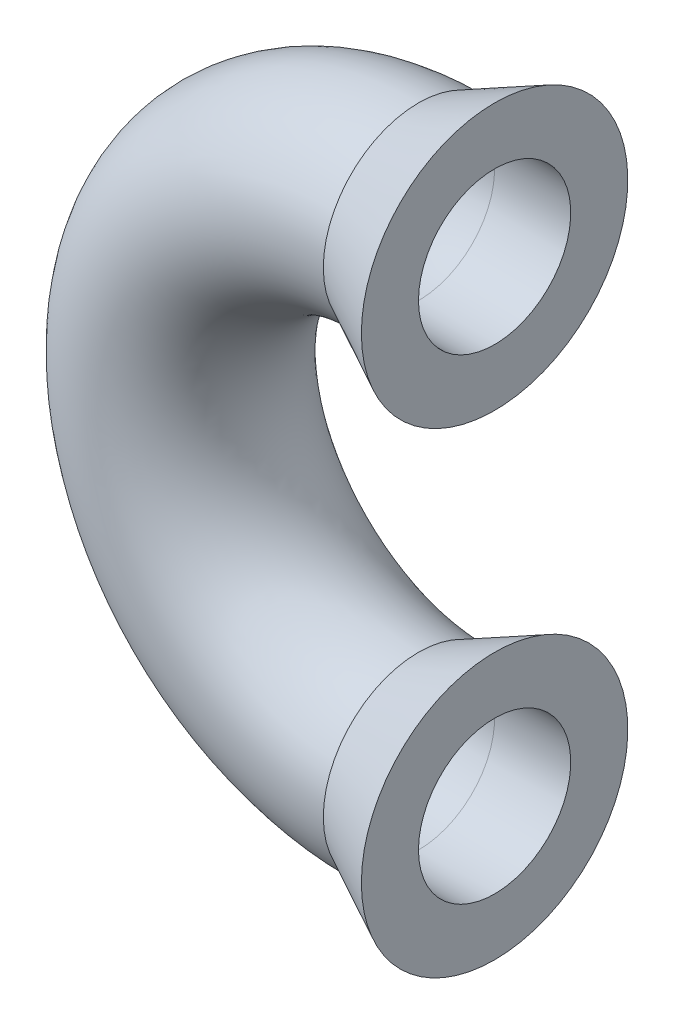
SolidWorks part; units mm, degrees
ref_plane "Спереди" through (0, 0, 0) normal (0, 0, 1) x (1, 0, 0)
ref_plane "Сверху" through (0, 0, 0) normal (0, 1, 0) x (1, 0, 0)
ref_plane "Справа" through (0, 0, 0) normal (1, 0, 0) x (0, 0, -1)
sketch "Эскиз1" plane through (0, 0, 0) normal (0, 0, 1) x (1, 0, 0)
  arc A15 (0, 12.5) -> (0, -12.5) centre (0, 0) ccw
sketch "Эскиз2" plane through (0, 0, 0) normal (1, 0, 0) x (0, 0, -1)
  line L0 (0, 12.5) -> (0, -12.5) construction
  circle A0 centre (0, 12.5) radius 5
  circle A1 centre (0, 12.5) radius 4
  dimension "D1" = 10
  dimension "D2" = 8
sweep "По траектории1" add profiles "Эскиз2" path "Эскиз1"
sketch "Эскиз3" plane through (0, 0, 0) normal (0, 0, 1) x (1, 0, 0)
  line L0 (4, 19.5) -> (0, 17.5)
  line L1 (4, 19.5) -> (4, 16.5)
  line L2 (0, 16.5) -> (4, 16.5)
  line L3 (0, 17.5) -> (0, 16.5)
  line L4 (-2.9153, 12.5) -> (6.2204, 12.5) construction
revolve "Повернуть1" add sketch "Эскиз3" angle 360 about L4
sketch "Эскиз5" plane through (0, 0, 0) normal (0, 0, 1) x (1, 0, 0)
  line L0 (4, -5.5) -> (0, -7.5)
  line L1 (4, -5.5) -> (4, -8.5)
  line L2 (0, -8.5) -> (4, -8.5)
  line L3 (0, -7.5) -> (0, -8.5)
  line L4 (-1.9765, -12.5) -> (5.6413, -12.5) construction
revolve "Повернуть2" add sketch "Эскиз5" angle 360 about L4
